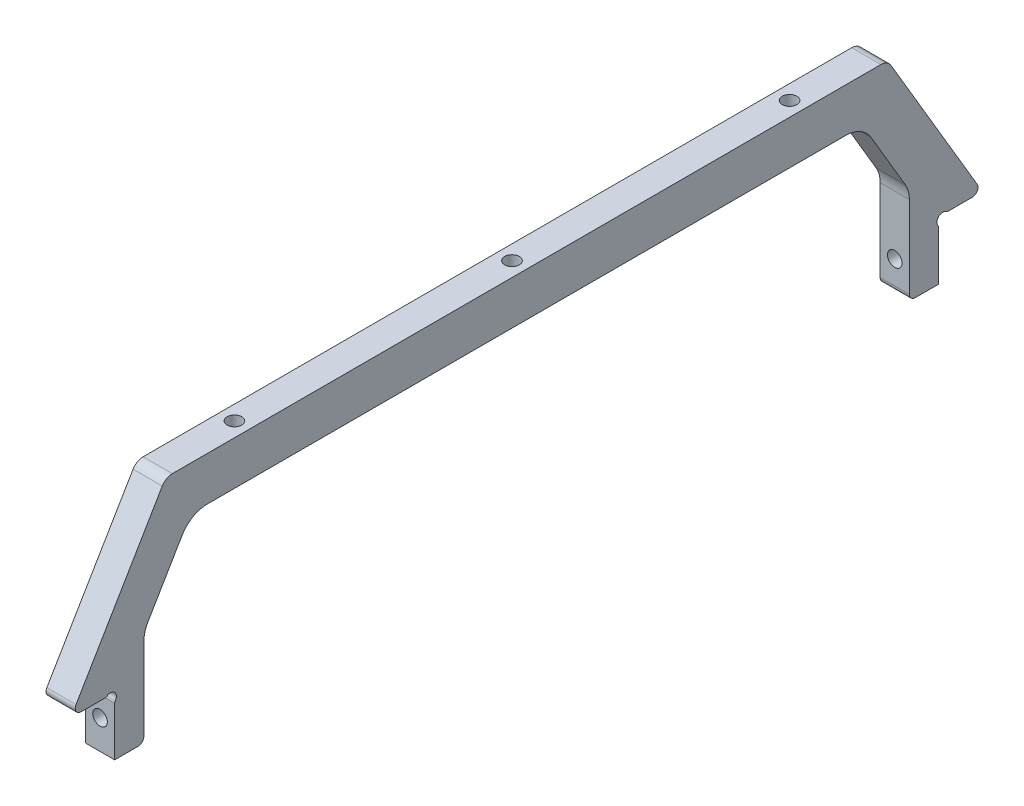
SolidWorks part; units mm, degrees
ref_plane "正面" through (0, 0, 0) normal (0, 0, 1) x (1, 0, 0)
ref_plane "平面" through (0, 0, 0) normal (0, 1, 0) x (1, 0, 0)
ref_plane "右側面" through (0, 0, 0) normal (1, 0, 0) x (0, 0, -1)
sketch "ｽｹｯﾁ1" plane through (0, 0, 0) normal (1, 0, 0) x (0, 0, -1)
  line L20 (-78, 5) -> (-60, 35.49)
  line L39 (-60, 35.49) -> (-60, 32.49)
  line L40 (-60, 32.49) -> (60, 32.49)
  line L41 (0, 32.49) -> (0, 24.99)
  line L42 (57.4893, 24.99) -> (-57.4893, 24.99)
  line L43 (-57.4893, 24.99) -> (-65.5, 11.4208)
  line L44 (-65.5, 11.4208) -> (-65.5, -5)
  line L45 (-65.5, -5) -> (-70.5, -5)
  line L46 (-70.5, -5) -> (-70.5, 5)
  line L47 (-70.5, 5) -> (-78, 5)
  line L48 (70.5, 5) -> (78, 5)
  line L49 (70.5, -5) -> (70.5, 5)
  line L50 (65.5, -5) -> (70.5, -5)
  line L51 (65.5, 11.4208) -> (65.5, -5)
  line L52 (57.4893, 24.99) -> (65.5, 11.4208)
  line L53 (60, 35.49) -> (60, 32.49)
  line L54 (78, 5) -> (60, 35.49)
  line L55 (-70.5, 5) -> (-71.2071, 4.2929) construction
  line L56 (-60, 32.49) -> (-59.2929, 33.1971) construction
  line L57 (60, 32.49) -> (59.2929, 33.1971) construction
  line L58 (70.5, 5) -> (71.2071, 4.2929) construction
  circle A0 centre (-71.2071, 4.2929) radius 1
  circle A1 centre (-59.2929, 33.1971) radius 1
  circle A2 centre (59.2929, 33.1971) radius 1
  circle A3 centre (71.2071, 4.2929) radius 1
  dimension "D1" = 45
  dimension "D2" = 2
  dimension "D4" = 2
  dimension "D3" = 45
extrude "ﾎﾞｽ - 押し出し1" add sketch "ｽｹｯﾁ1" along normal mid plane 5 contours L47 L46 L45 L44 L43 L42 L41 L40 L39 L20 | L48 L54 L53 L40 L41 L42 L52 L51 L50 L49
fillet "ﾌｨﾚｯﾄ1" radius 1 6 edges at (0, 35.49, -60) (0, 5, -78) (0, -5, -65.5) (0, -5, 65.5) (0, 35.49, 60) (0, 5, 78)
fillet "ﾌｨﾚｯﾄ2" radius 0.5 4 edges at (0, 32.49, 58.5858) (0, 33.9042, 60) (0, 3.5858, 70.5) (0, 5, 71.9142)
fillet "ﾌｨﾚｯﾄ3" radius 0.5 4 edges at (0, 3.5858, -70.5) (0, 5, -71.9142) (0, 33.9042, -60) (0, 32.49, -58.5858)
sketch "ｽｹｯﾁ2" plane through (0, 32.49, 0) normal (0, 1, 0) x (1, 0, 0)
  line L0 (0, -55) -> (0, 55) construction
  line L1 (0, 0) -> (2.5, 0) construction
  line L2 (2.5, -58.4024) -> (2.5, 58.4024) construction
  circle A0 centre (0, -47.5) radius 1.25
  circle A1 centre (0, 0) radius 1.25
  circle A2 centre (0, 47.5) radius 1.25
  dimension "D1" = 2.5
  dimension "D2" = 2.5
  dimension "D3" = 47.5
extrude "ｶｯﾄ - 押し出し1" cut sketch "ｽｹｯﾁ2" against normal blind 7.5
sketch "ｽｹｯﾁ3" plane through (0, 0, 70.5) normal (0, 0, 1) x (1, 0, 0)
  line L0 (0, -5) -> (0, 5) construction
  line L1 (2.5, -5) -> (-2.5, -5) construction
  circle A0 centre (0, 0) radius 1.25
  dimension "D1" = 2.5
  dimension "D2" = 5
extrude "ｶｯﾄ - 押し出し2" cut sketch "ｽｹｯﾁ3" against normal blind 200
fillet "ﾌｨﾚｯﾄ4" radius 5 4 edges at (0, 11.4208, 65.5) (0, 24.99, 57.4893) (0, 24.99, -57.4893) (0, 11.4208, -65.5)
sketch "ｽｹｯﾁ4" plane through (-2.5, 0, 0) normal (-1, 0, 0) x (0, 0, 1)
  line L0 (-61.7711, 32.49) -> (61.7711, 32.49)
  line L14 (-70.5, 3.4024) -> (-70.5, -5)
  line L15 (-70.5, -5) -> (-66.5, -5)
  line L16 (-65.5, -4) -> (-65.5, 10.055)
  line L17 (-64.8057, 12.5969) -> (-58.9405, 22.5319)
  line L18 (-54.6348, 24.99) -> (54.6348, 24.99)
  line L19 (58.9405, 22.5319) -> (64.8057, 12.5969)
  line L20 (65.5, 10.055) -> (65.5, -4)
  line L21 (66.5, -5) -> (70.5, -5)
  line L22 (70.5, -5) -> (70.5, 3.4024)
  line L23 (72.0976, 5) -> (76.2484, 5)
  line L24 (77.1095, 6.5084) -> (61.2231, 33.4182)
  line L25 (58.4024, 32.49) -> (-58.4024, 32.49)
  line L26 (-61.2231, 33.4182) -> (-77.1095, 6.5084)
  line L27 (-76.2484, 5) -> (-72.0976, 5)
  line L28 (-70.5, 3.4024) -> (-70.5, -5)
  line L29 (-70.5, -5) -> (-66.5, -5)
  line L30 (-65.5, -4) -> (-65.5, 10.055)
  line L31 (-64.8057, 12.5969) -> (-58.9405, 22.5319)
  line L32 (-54.6348, 24.99) -> (54.6348, 24.99)
  line L33 (58.9405, 22.5319) -> (64.8057, 12.5969)
  line L34 (65.5, 10.055) -> (65.5, -4)
  line L35 (66.5, -5) -> (70.5, -5)
  line L36 (70.5, -5) -> (70.5, 3.4024)
  line L37 (72.0976, 5) -> (76.2484, 5)
  line L38 (77.1095, 6.5084) -> (61.2231, 33.4182)
  line L39 (58.4024, 32.49) -> (-58.4024, 32.49)
  line L40 (-61.2231, 33.4182) -> (-77.1095, 6.5084)
  line L41 (-76.2484, 5) -> (-72.0976, 5)
  arc A20 (-70.4024, 3.6993) -> (-71.8007, 5.0976) centre (-71.2071, 4.2929) ccw
  arc A21 (-70.4024, 3.6993) -> (-70.5, 3.4024) centre (-70, 3.4024) ccw
  arc A22 (-66.5, -5) -> (-65.5, -4) centre (-66.5, -4) ccw
  arc A23 (-64.8057, 12.5969) -> (-65.5, 10.055) centre (-60.5, 10.055) ccw
  arc A24 (-54.6348, 24.99) -> (-58.9405, 22.5319) centre (-54.6348, 19.99) ccw
  arc A25 (58.9405, 22.5319) -> (54.6348, 24.99) centre (54.6348, 19.99) ccw
  arc A26 (65.5, 10.055) -> (64.8057, 12.5969) centre (60.5, 10.055) ccw
  arc A27 (65.5, -4) -> (66.5, -5) centre (66.5, -4) ccw
  arc A28 (70.5, 3.4024) -> (70.4024, 3.6993) centre (70, 3.4024) ccw
  arc A29 (71.8007, 5.0976) -> (70.4024, 3.6993) centre (71.2071, 4.2929) ccw
  arc A30 (71.8007, 5.0976) -> (72.0976, 5) centre (72.0976, 5.5) ccw
  arc A31 (76.2484, 5) -> (77.1095, 6.5084) centre (76.2484, 6) ccw
  arc A32 (61.2231, 33.4182) -> (60.2926, 33.1751) centre (60.7925, 33.164) ccw
  arc A33 (58.6993, 32.3924) -> (60.2926, 33.1751) centre (59.2929, 33.1971) ccw
  arc A34 (58.6993, 32.3924) -> (58.4024, 32.49) centre (58.4024, 31.99) ccw
  arc A35 (-58.4024, 32.49) -> (-58.6993, 32.3924) centre (-58.4024, 31.99) ccw
  arc A36 (-60.2926, 33.1751) -> (-58.6993, 32.3924) centre (-59.2929, 33.1971) ccw
  arc A37 (-60.2926, 33.1751) -> (-61.2231, 33.4182) centre (-60.7925, 33.164) ccw
  arc A38 (-77.1095, 6.5084) -> (-76.2484, 5) centre (-76.2484, 6) ccw
  arc A39 (-72.0976, 5) -> (-71.8007, 5.0976) centre (-72.0976, 5.5) ccw
  arc A40 (-70.4024, 3.6993) -> (-71.8007, 5.0976) centre (-71.2071, 4.2929) ccw
  arc A41 (-70.4024, 3.6993) -> (-70.5, 3.4024) centre (-70, 3.4024) ccw
  arc A42 (-66.5, -5) -> (-65.5, -4) centre (-66.5, -4) ccw
  arc A43 (-64.8057, 12.5969) -> (-65.5, 10.055) centre (-60.5, 10.055) ccw
  arc A44 (-54.6348, 24.99) -> (-58.9405, 22.5319) centre (-54.6348, 19.99) ccw
  arc A45 (58.9405, 22.5319) -> (54.6348, 24.99) centre (54.6348, 19.99) ccw
  arc A46 (65.5, 10.055) -> (64.8057, 12.5969) centre (60.5, 10.055) ccw
  arc A47 (65.5, -4) -> (66.5, -5) centre (66.5, -4) ccw
  arc A48 (70.5, 3.4024) -> (70.4024, 3.6993) centre (70, 3.4024) ccw
  arc A49 (71.8007, 5.0976) -> (70.4024, 3.6993) centre (71.2071, 4.2929) ccw
  arc A50 (71.8007, 5.0976) -> (72.0976, 5) centre (72.0976, 5.5) ccw
  arc A51 (76.2484, 5) -> (77.1095, 6.5084) centre (76.2484, 6) ccw
  arc A52 (61.2231, 33.4182) -> (60.2926, 33.1751) centre (60.7925, 33.164) ccw
  arc A53 (58.6993, 32.3924) -> (60.2926, 33.1751) centre (59.2929, 33.1971) ccw
  arc A54 (58.6993, 32.3924) -> (58.4024, 32.49) centre (58.4024, 31.99) ccw
  arc A55 (-58.4024, 32.49) -> (-58.6993, 32.3924) centre (-58.4024, 31.99) ccw
  arc A56 (-60.2926, 33.1751) -> (-58.6993, 32.3924) centre (-59.2929, 33.1971) ccw
  arc A57 (-60.2926, 33.1751) -> (-61.2231, 33.4182) centre (-60.7925, 33.164) ccw
  arc A58 (-77.1095, 6.5084) -> (-76.2484, 5) centre (-76.2484, 6) ccw
  arc A59 (-72.0976, 5) -> (-71.8007, 5.0976) centre (-72.0976, 5.5) ccw
  point P10 (-61.3063, 33.2772)
  line M58 (77.1095, 6.5084) -> (61.2231, 33.4182)
  arc M59 (61.2231, 33.4182) -> (60.2926, 33.1751) centre (60.7925, 33.164) ccw
  arc M60 (60.2926, 33.1751) -> (58.6993, 32.3924) centre (59.2929, 33.1971) cw
  arc M64 (-58.6993, 32.3924) -> (-60.2926, 33.1751) centre (-59.2929, 33.1971) cw
  arc M65 (-60.2926, 33.1751) -> (-61.2231, 33.4182) centre (-60.7925, 33.164) ccw
  line M66 (-61.2231, 33.4182) -> (-77.1095, 6.5084)
  dimension "D1" = 0
extrude "ｶｯﾄ - 押し出し3" cut sketch "ｽｹｯﾁ4" against normal blind 10 contours L0 M66 M64 M65 | L0 M60 M58 M59
sketch "ｽｹｯﾁ5" plane through (-2.5, 0, 0) normal (-1, 0, 0) x (0, 0, 1)
  line L0 (-61.7711, 32.49) -> (61.7711, 32.49) construction
  line L1 (-61.7711, 32.49) -> (61.7711, 32.49)
  line L14 (-76.2484, 5) -> (-72.0976, 5)
  line L15 (-70.5, 3.4024) -> (-70.5, -5)
  line L16 (-70.5, -5) -> (-66.5, -5)
  line L17 (-65.5, -4) -> (-65.5, 10.055)
  line L18 (-64.8057, 12.5969) -> (-58.9405, 22.5319)
  line L19 (-54.6348, 24.99) -> (54.6348, 24.99)
  line L20 (58.9405, 22.5319) -> (64.8057, 12.5969)
  line L21 (65.5, 10.055) -> (65.5, -4)
  line L22 (66.5, -5) -> (70.5, -5)
  line L23 (70.5, -5) -> (70.5, 3.4024)
  line L24 (72.0976, 5) -> (76.2484, 5)
  line L25 (77.1095, 6.5084) -> (61.2231, 33.4182)
  line L26 (58.4024, 32.49) -> (-58.4024, 32.49)
  line L27 (-61.2231, 33.4182) -> (-77.1095, 6.5084)
  line L28 (-76.2484, 5) -> (-72.0976, 5)
  line L29 (-70.5, 3.4024) -> (-70.5, -5)
  line L30 (-70.5, -5) -> (-66.5, -5)
  line L31 (-65.5, -4) -> (-65.5, 10.055)
  line L32 (-64.8057, 12.5969) -> (-58.9405, 22.5319)
  line L33 (-54.6348, 24.99) -> (54.6348, 24.99)
  line L34 (58.9405, 22.5319) -> (64.8057, 12.5969)
  line L35 (65.5, 10.055) -> (65.5, -4)
  line L36 (66.5, -5) -> (70.5, -5)
  line L37 (70.5, -5) -> (70.5, 3.4024)
  line L38 (72.0976, 5) -> (76.2484, 5)
  line L39 (77.1095, 6.5084) -> (61.2231, 33.4182)
  line L40 (58.4024, 32.49) -> (-58.4024, 32.49)
  line L41 (-61.2231, 33.4182) -> (-77.1095, 6.5084)
  arc A20 (-72.0976, 5) -> (-71.8007, 5.0976) centre (-72.0976, 5.5) ccw
  arc A21 (-70.4024, 3.6993) -> (-71.8007, 5.0976) centre (-71.2071, 4.2929) ccw
  arc A22 (-70.4024, 3.6993) -> (-70.5, 3.4024) centre (-70, 3.4024) ccw
  arc A23 (-66.5, -5) -> (-65.5, -4) centre (-66.5, -4) ccw
  arc A24 (-64.8057, 12.5969) -> (-65.5, 10.055) centre (-60.5, 10.055) ccw
  arc A25 (-54.6348, 24.99) -> (-58.9405, 22.5319) centre (-54.6348, 19.99) ccw
  arc A26 (58.9405, 22.5319) -> (54.6348, 24.99) centre (54.6348, 19.99) ccw
  arc A27 (65.5, 10.055) -> (64.8057, 12.5969) centre (60.5, 10.055) ccw
  arc A28 (65.5, -4) -> (66.5, -5) centre (66.5, -4) ccw
  arc A29 (70.5, 3.4024) -> (70.4024, 3.6993) centre (70, 3.4024) ccw
  arc A30 (71.8007, 5.0976) -> (70.4024, 3.6993) centre (71.2071, 4.2929) ccw
  arc A31 (71.8007, 5.0976) -> (72.0976, 5) centre (72.0976, 5.5) ccw
  arc A32 (76.2484, 5) -> (77.1095, 6.5084) centre (76.2484, 6) ccw
  arc A33 (61.2231, 33.4182) -> (60.2926, 33.1751) centre (60.7925, 33.164) ccw
  arc A34 (58.6993, 32.3924) -> (60.2926, 33.1751) centre (59.2929, 33.1971) ccw
  arc A35 (58.6993, 32.3924) -> (58.4024, 32.49) centre (58.4024, 31.99) ccw
  arc A36 (-58.4024, 32.49) -> (-58.6993, 32.3924) centre (-58.4024, 31.99) ccw
  arc A37 (-60.2926, 33.1751) -> (-58.6993, 32.3924) centre (-59.2929, 33.1971) ccw
  arc A38 (-60.2926, 33.1751) -> (-61.2231, 33.4182) centre (-60.7925, 33.164) ccw
  arc A39 (-77.1095, 6.5084) -> (-76.2484, 5) centre (-76.2484, 6) ccw
  arc A40 (-72.0976, 5) -> (-71.8007, 5.0976) centre (-72.0976, 5.5) ccw
  arc A41 (-70.4024, 3.6993) -> (-71.8007, 5.0976) centre (-71.2071, 4.2929) ccw
  arc A42 (-70.4024, 3.6993) -> (-70.5, 3.4024) centre (-70, 3.4024) ccw
  arc A43 (-66.5, -5) -> (-65.5, -4) centre (-66.5, -4) ccw
  arc A44 (-64.8057, 12.5969) -> (-65.5, 10.055) centre (-60.5, 10.055) ccw
  arc A45 (-54.6348, 24.99) -> (-58.9405, 22.5319) centre (-54.6348, 19.99) ccw
  arc A46 (58.9405, 22.5319) -> (54.6348, 24.99) centre (54.6348, 19.99) ccw
  arc A47 (65.5, 10.055) -> (64.8057, 12.5969) centre (60.5, 10.055) ccw
  arc A48 (65.5, -4) -> (66.5, -5) centre (66.5, -4) ccw
  arc A49 (70.5, 3.4024) -> (70.4024, 3.6993) centre (70, 3.4024) ccw
  arc A50 (71.8007, 5.0976) -> (70.4024, 3.6993) centre (71.2071, 4.2929) ccw
  arc A51 (71.8007, 5.0976) -> (72.0976, 5) centre (72.0976, 5.5) ccw
  arc A52 (76.2484, 5) -> (77.1095, 6.5084) centre (76.2484, 6) ccw
  arc A53 (61.2231, 33.4182) -> (60.2926, 33.1751) centre (60.7925, 33.164) ccw
  arc A54 (58.6993, 32.3924) -> (60.2926, 33.1751) centre (59.2929, 33.1971) ccw
  arc A55 (58.6993, 32.3924) -> (58.4024, 32.49) centre (58.4024, 31.99) ccw
  arc A56 (-58.4024, 32.49) -> (-58.6993, 32.3924) centre (-58.4024, 31.99) ccw
  arc A57 (-60.2926, 33.1751) -> (-58.6993, 32.3924) centre (-59.2929, 33.1971) ccw
  arc A58 (-60.2926, 33.1751) -> (-61.2231, 33.4182) centre (-60.7925, 33.164) ccw
  arc A59 (-77.1095, 6.5084) -> (-76.2484, 5) centre (-76.2484, 6) ccw
  arc M35 (-58.6993, 32.3924) -> (-60, 32.49) centre (-59.2929, 33.1971) cw
  arc M65 (60, 32.49) -> (58.6993, 32.3924) centre (59.2929, 33.1971) cw
  arc M66 (58.6993, 32.3924) -> (58.4024, 32.49) centre (58.4024, 31.99) ccw
  arc M68 (-58.4024, 32.49) -> (-58.6993, 32.3924) centre (-58.4024, 31.99) ccw
  dimension "D1" = 0
extrude "ﾎﾞｽ - 押し出し2" add sketch "ｽｹｯﾁ5" against normal up to surface (5 mm away) contours L1 M35 M68 | L1 M66 M65
fillet "ﾌｨﾚｯﾄ5" radius 2 2 edges at (0, 32.49, 61.7711) (0, 32.49, -61.7711)
